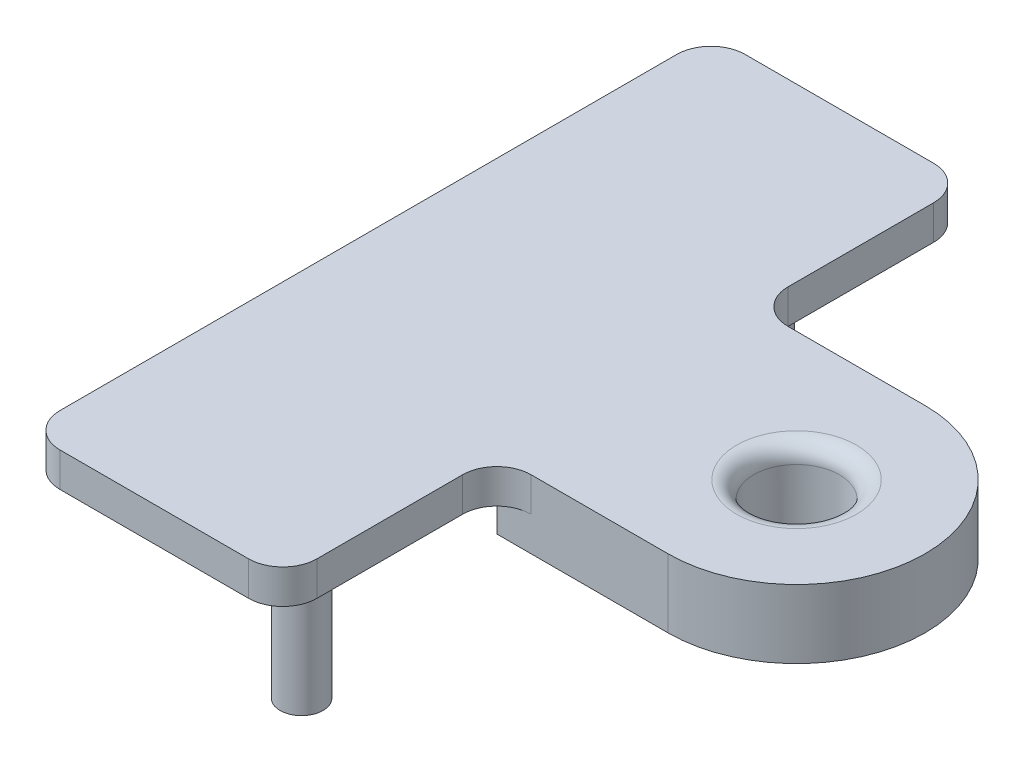
SolidWorks part; units mm, degrees
ref_plane "前视基准面" through (0, 0, 0) normal (0, 0, 1) x (1, 0, 0)
ref_plane "上视基准面" through (0, 0, 0) normal (0, 1, 0) x (1, 0, 0)
ref_plane "右视基准面" through (0, 0, 0) normal (1, 0, 0) x (0, 0, -1)
other "Configuration Table"
sketch "草图1" plane through (0, 0, 0) normal (0, 1, 0) x (1, 0, 0)
  line L0 (0, 0) -> (27.4436, 0) construction
  line L1 (-7.5, -20) -> (7.5, -20)
  line L2 (-7.5, -20) -> (-7.5, 20)
  line L3 (-7.5, 20) -> (7.5, 20)
  line L4 (7.5, -20) -> (7.5, 20)
  line L5 (-7.5, -20) -> (7.5, 20) construction
  line L6 (-7.5, 20) -> (7.5, -20) construction
  point P0 (0, 0)
  dimension "D1" = 15
  dimension "D2" = 40
extrude "凸台-拉伸1" add sketch "草图1" along normal blind 2
sketch "草图2" plane through (0, 2, 0) normal (0, 1, 0) x (1, 0, 0)
  line L0 (0, 0) -> (33.7488, 0) construction
  line L1 (7.5, 0) -> (17.5, 0) construction
  line L2 (7.5, -20) -> (7.5, 20) construction
  line L4 (7.5, -7.5) -> (17.5, -7.5)
  line L5 (7.5, 7.5) -> (7.5, -7.5)
  line L6 (7.5, -20) -> (7.5, 20) construction
  line L7 (17.5, 7.5) -> (7.5, 7.5)
  arc A1 (17.5, -7.5) -> (17.5, 7.5) centre (17.5, 0) ccw
  point P6 (14.2593, 0)
  point P11 (0, 0)
  point P12 (20.315, 0)
  dimension "D2" = 10
  dimension "D1" = 15
extrude "凸台-拉伸2" add sketch "草图2" against normal blind 4
sketch "草图3" plane through (0, 0, 0) normal (0, -1, 0) x (1, 0, 0)
  line L0 (-7.5, 0) -> (31.8643, 0) construction
  line L1 (7.5, 20) -> (7.5, 7.5) construction
  circle A0 centre (2.1, 13.5) radius 1.25
  circle A1 centre (2.1, -13.5) radius 1.25
  dimension "D1" = 2.5
  dimension "D2" = 27
  dimension "D3" = 5.4
extrude "凸台-拉伸3" add sketch "草图3" along normal blind 10
sketch "草图4" plane through (0, 2, 0) normal (0, 1, 0) x (1, 0, 0)
  circle A0 centre (17.5, 0) radius 2.5
  arc A1 (17.5, -7.5) -> (17.5, 7.5) centre (17.5, 0) ccw construction
  point P2 (0, 0)
  dimension "D1" = 5
extrude "切除-拉伸1" cut sketch "草图4" against normal up to next
fillet "圆角2" radius 1 1 edges at (17.5, 2, 2.5)
fillet "圆角3" radius 2 6 edges at (-7.5, 1, -20) (7.5, 1, -20) (7.5, 1, 7.5) (7.5, 1, -7.5) (7.5, 1, 20) (-7.5, 1, 20)
